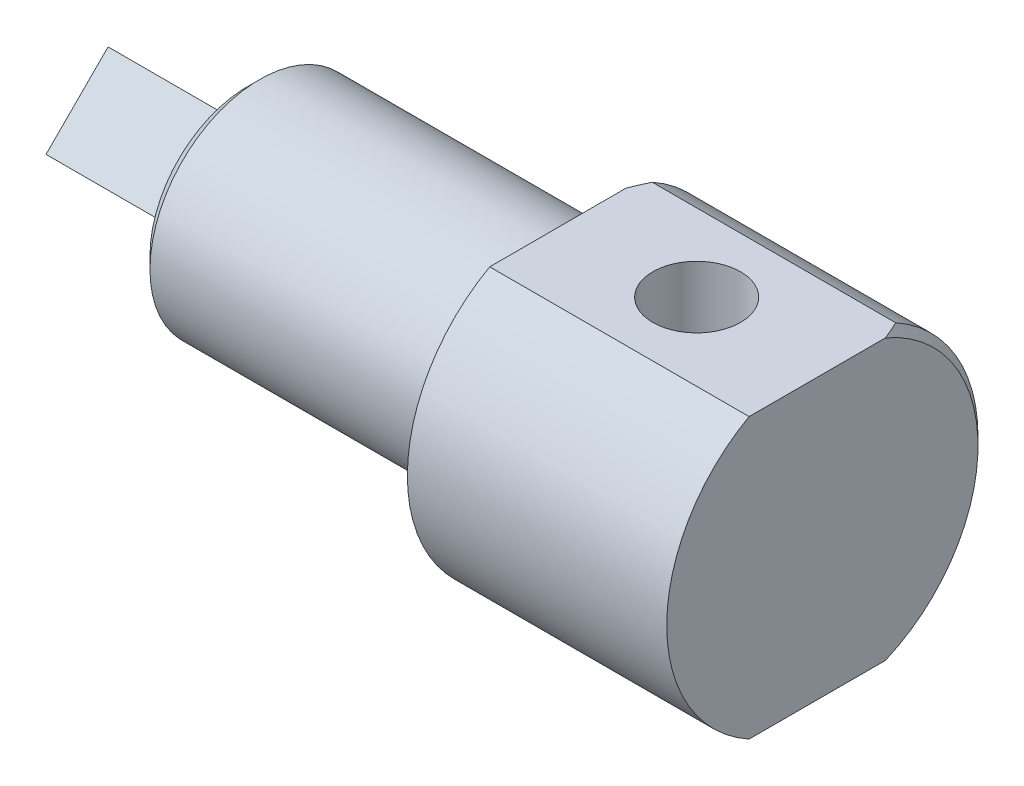
SolidWorks part; units mm, degrees
ref_plane "Спереди" through (0, 0, 0) normal (0, 0, 1) x (1, 0, 0)
ref_plane "Сверху" through (0, 0, 0) normal (0, 1, 0) x (1, 0, 0)
ref_plane "Справа" through (0, 0, 0) normal (1, 0, 0) x (0, 0, -1)
sketch "Эскиз1" plane through (0, 0, 0) normal (0, 0, 1) x (1, 0, 0)
  line L0 (0, 0) -> (-9.5781, 0) construction
  line L1 (0, 0) -> (0, 27.5)
  line L2 (0, 27.5) -> (80, 27.5)
  line L3 (80, 27.5) -> (80, 40)
  line L4 (80, 40) -> (145, 40)
  line L5 (145, 40) -> (145, 0)
  line L6 (145, 0) -> (0, 0)
  dimension "D1" = 145
  dimension "D2" = 80
  dimension "D3" = 80
  dimension "D4" = 55
revolve "Повернуть1" add sketch "Эскиз1" angle 360 about L0
sketch "Эскиз3" plane through (0, 0, 0) normal (-1, 0, 0) x (0, 0, 1)
  line L0 (0, 27.5) -> (0, -27.5) construction
  line L1 (-27.5, 0) -> (27.5, 0) construction
  line L2 (0, -15.5563) -> (-15.5563, 0)
  line L3 (0, -15.5563) -> (15.5563, 0)
  line L4 (-15.5563, 0) -> (0, 15.5563)
  line L5 (15.5563, 0) -> (0, 15.5563)
  line L6 (0, -15.5563) -> (0, 15.5563) construction
  line L7 (-15.5563, 0) -> (15.5563, 0) construction
  circle A0 centre (0, 0) radius 27.5 construction
  circle A1 centre (0, 0) radius 27.5 construction
  point P10 (0, 0)
  dimension "D1" = 22
extrude "Бобышка-Вытянуть1" add sketch "Эскиз3" along normal blind 35
sketch "Эскиз4" plane through (0, 0, 0) normal (0, 1, 0) x (1, 0, 0)
  line L0 (80, 27.5) -> (0, 27.5) construction
  line L1 (15, 27.5) -> (60, 27.5)
  line L2 (15, 27.5) -> (15, 22.5)
  line L3 (15, 22.5) -> (60, 22.5)
  line L4 (60, 27.5) -> (60, 22.5)
  line L6 (0, 27.5) -> (0, -27.5) construction
  dimension "D1" = 45
  dimension "D2" = 5
  dimension "D3" = 15
extrude "Вырез-Вытянуть1" cut sketch "Эскиз4" against normal mid plane 16
sketch "Эскиз5" plane through (145, 0, 0) normal (1, 0, 0) x (0, 0, -1)
  line L0 (-19.3649, 35) -> (19.3649, 35)
  line L1 (-40, 0) -> (40, 0) construction
  circle A0 centre (0, 0) radius 40 construction
  dimension "D1" = 70
extrude "Вырез-Вытянуть2" cut sketch "Эскиз5" against normal through all and the other way through all
mirror "Зеркальное отражение1" about plane through (0, 0, 0) normal (0, 1, 0) of "Вырез-Вытянуть2"
sketch "Эскиз6" plane through (0, 35, 0) normal (0, 1, 0) x (1, 0, 0)
  line L0 (80, 40) -> (80, 19.3649) construction
  line L1 (80, 0) -> (145, 0) construction
  line L2 (80, 27.5) -> (80, -27.5) construction
  line L3 (145, 19.3649) -> (145, -19.3649) construction
  circle A0 centre (112.5, 0) radius 11
  dimension "D2" = 22
  dimension "D1" = 32.5
extrude "Вырез-Вытянуть3" cut sketch "Эскиз6" against normal through all both and the other way through all
chamfer "Фаска1" distance 2 angle 45 2 edges at (145, 0, -40) (80, 0, -40)
chamfer "Фаска2" distance 3 angle 45 1 edges at (0, 0, -27.5)
